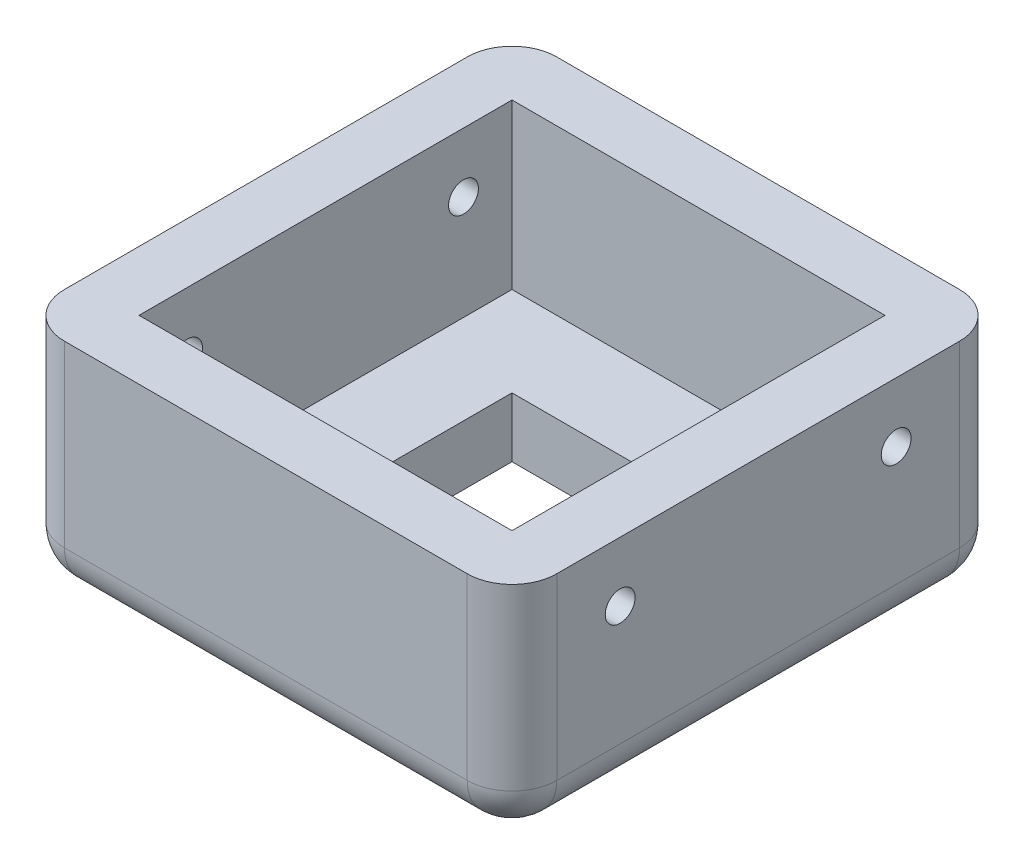
SolidWorks part; units mm, degrees
material "PBT Общее назначение"
ref_plane "Спереди" through (0, 0, 0) normal (0, 0, 1) x (1, 0, 0)
ref_plane "Сверху" through (0, 0, 0) normal (0, 1, 0) x (1, 0, 0)
ref_plane "Справа" through (0, 0, 0) normal (1, 0, 0) x (0, 0, -1)
sketch "Эскиз1" plane through (0, 0, 0) normal (0, 1, 0) x (1, 0, 0)
  line L0 (0, 0) -> (13, 0)
  line L1 (0, 0) -> (0, 13)
  line L2 (13, 0) -> (13, 13)
  line L3 (0, 13) -> (13, 13)
  line L4 (-10, 23) -> (23, 23)
  line L5 (-10, 23) -> (-10, -10)
  line L6 (23, 23) -> (23, -10)
  line L7 (-10, -10) -> (23, -10)
  line L8 (6.5, 23) -> (6.5, -10) construction
  line L9 (23, 6.5) -> (-10, 6.5) construction
  line L10 (6.5, 13) -> (6.5, 0) construction
  line L11 (13, 6.5) -> (0, 6.5) construction
  dimension "D1" = 13
  dimension "D2" = 13
  dimension "D3" = 33
  dimension "D4" = 33
extrude "Бобышка-Вытянуть1" add sketch "Эскиз1" along normal blind 15
sketch "Эскиз2" plane through (0, 15, 0) normal (0, 1, 0) x (1, 0, 0)
  line L0 (-6, 19) -> (19, 19)
  line L1 (-6, 19) -> (-6, -6)
  line L2 (19, 19) -> (19, -6)
  line L3 (-6, -6) -> (19, -6)
  line L4 (19, 6.5) -> (-6, 6.5) construction
  line L5 (6.5, 19) -> (6.5, -6) construction
  line L6 (13, 13) -> (0, 13) construction
  line L7 (13, 0) -> (13, 13) construction
  point P8 (6.5, 13)
  point P9 (13, 6.5)
  dimension "D1" = 25
  dimension "D2" = 25
extrude "Вырез-Вытянуть1" cut sketch "Эскиз2" against normal blind 11
fillet "Скругление3" radius 3 8 edges at (-10, 7.5, -23) (-10, 7.5, 10) (-10, 0, -6.5) (6.5, 0, -23) (23, 7.5, -23) (23, 0, -6.5) (23, 7.5, 10) (6.5, 0, 10)
sketch "Эскиз3" plane through (-10, 0, 0) normal (-1, 0, 0) x (0, 0, 1)
  circle A0 centre (2.75, 10) radius 1 construction
  circle A1 centre (2.75, 10) radius 1 construction
  circle A2 centre (-15.75, 10) radius 1 construction
  circle A3 centre (-15.75, 10) radius 1 construction
sketch "Эскиз4" plane through (-10, 0, 0) normal (-1, 0, 0) x (0, 0, 1)
  line L0 (2.75, 10) -> (2.75, 7.0387) construction
  line L1 (-15.75, 10) -> (-15.75, 7.0387) construction
  line L2 (2.75, 11) -> (-15.75, 11) construction
  line L3 (-20, 15) -> (7, 15) construction
  circle A0 centre (2.75, 11) radius 1
  circle A1 centre (-15.75, 11) radius 1
  dimension "D1" = 4
  dimension "D3" = 2
  dimension "D4" = 2
extrude "Вырез-Вытянуть2" cut sketch "Эскиз4" against normal through all
sketch "Эскиз5" plane through (0, 15, 0) normal (0, 1, 0) x (1, 0, 0)
  line L0 (-10, 6.5) -> (23, 6.5) construction
  line L1 (-10, 20) -> (-10, -7) construction
  line L2 (23, -7) -> (23, 20) construction
  line L3 (6.5, 23) -> (6.5, -10) construction
  line L4 (20, 23) -> (-7, 23) construction
  line L5 (-7, -10) -> (20, -10) construction
